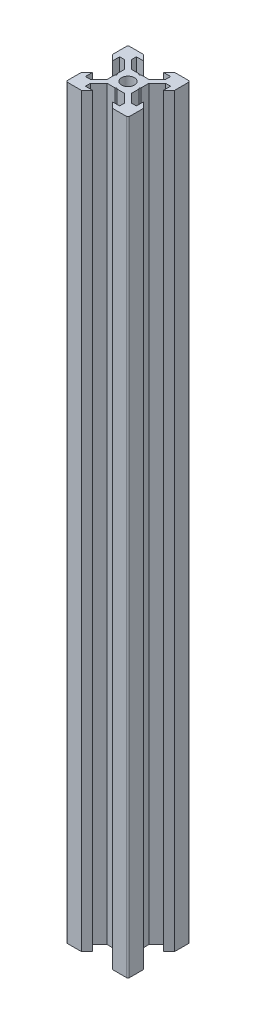
SolidWorks part; units mm, degrees
material "6063-O，挤压棒材(SS)"
ref_plane "前视基准面" through (0, 0, 0) normal (0, 0, 1) x (1, 0, 0)
ref_plane "上视基准面" through (0, 0, 0) normal (0, 1, 0) x (1, 0, 0)
ref_plane "右视基准面" through (0, 0, 0) normal (1, 0, 0) x (0, 0, -1)
other "Configuration Table"
sketch "草图1" plane through (0, 0, 0) normal (0, 1, 0) x (1, 0, 0)
  line L0 (-2.0109, 3.9) -> (2.0109, 3.9)
  line L1 (3.4251, 4.4858) -> (5.5, 6.5607)
  line L2 (5.5, 6.5607) -> (5.5, 8.2)
  line L3 (5.5, 8.2) -> (3.3, 8.2)
  line L4 (3.1, 8.4) -> (3.1, 9.3)
  line L5 (3.8, 10) -> (8.5, 10)
  line L6 (10, 8.5) -> (10, 3.8)
  line L7 (9.3, 3.1) -> (8.4, 3.1)
  line L8 (8.2, 3.3) -> (8.2, 5.5)
  line L9 (8.2, 5.5) -> (6.5607, 5.5)
  line L10 (6.5607, 5.5) -> (4.4858, 3.4251)
  line L11 (3.9, 2.0109) -> (3.9, -2.0109)
  line L12 (4.4858, -3.4251) -> (6.5607, -5.5)
  line L13 (6.5607, -5.5) -> (8.2, -5.5)
  line L14 (8.2, -5.5) -> (8.2, -3.3)
  line L15 (8.4, -3.1) -> (9.3, -3.1)
  line L16 (10, -3.8) -> (10, -8.5)
  line L17 (8.5, -10) -> (3.8, -10)
  line L18 (3.1, -9.3) -> (3.1, -8.4)
  line L19 (3.3, -8.2) -> (5.5, -8.2)
  line L20 (5.5, -8.2) -> (5.5, -6.5607)
  line L21 (5.5, -6.5607) -> (3.4251, -4.4858)
  line L22 (2.0109, -3.9) -> (-2.0109, -3.9)
  line L23 (-3.4251, -4.4858) -> (-5.5, -6.5607)
  line L24 (-5.5, -6.5607) -> (-5.5, -8.2)
  line L25 (-5.5, -8.2) -> (-3.3, -8.2)
  line L26 (-3.1, -8.4) -> (-3.1, -9.3)
  line L27 (-3.8, -10) -> (-8.5, -10)
  line L28 (-10, -8.5) -> (-10, -3.8)
  line L29 (-9.3, -3.1) -> (-8.4, -3.1)
  line L30 (-8.2, -3.3) -> (-8.2, -5.5)
  line L31 (-8.2, -5.5) -> (-6.5607, -5.5)
  line L32 (-6.5607, -5.5) -> (-4.4858, -3.4251)
  line L33 (-3.9, -2.0109) -> (-3.9, 2.0109)
  line L34 (-4.4858, 3.4251) -> (-6.5607, 5.5)
  line L35 (-6.5607, 5.5) -> (-8.2, 5.5)
  line L36 (-8.2, 5.5) -> (-8.2, 3.3)
  line L37 (-8.4, 3.1) -> (-9.3, 3.1)
  line L38 (-10, 3.8) -> (-10, 8.5)
  line L39 (-8.5, 10) -> (-3.8, 10)
  line L40 (-3.1, 9.3) -> (-3.1, 8.4)
  line L41 (-3.3, 8.2) -> (-5.5, 8.2)
  line L42 (-5.5, 8.2) -> (-5.5, 6.5607)
  line L43 (-5.5, 6.5607) -> (-3.4251, 4.4858)
  line L44 (-4.4858, 3.4251) -> (-3.4251, 4.4858) construction
  line L45 (3.4251, 4.4858) -> (4.4858, 3.4251) construction
  line L46 (4.4858, -3.4251) -> (3.4251, -4.4858) construction
  line L47 (-3.4251, -4.4858) -> (-4.4858, -3.4251) construction
  line L48 (3.9555, -3.9555) -> (-3.9555, 3.9555) construction
  line L49 (3.9555, 3.9555) -> (-3.9555, -3.9555) construction
  line L50 (-9.5, 3.3) -> (-9.5, 3.6)
  line L51 (-9.5, 3.6) -> (-9.8, 3.6)
  line L52 (-3.6, 9.8) -> (-3.6, 9.5)
  line L53 (-3.6, 9.5) -> (-3.3, 9.5)
  line L54 (3.3, 9.5) -> (3.6, 9.5)
  line L55 (3.6, 9.5) -> (3.6, 9.8)
  line L56 (9.5, 3.3) -> (9.5, 3.6)
  line L57 (9.5, 3.6) -> (9.8, 3.6)
  line L58 (9.5, -3.3) -> (9.5, -3.6)
  line L59 (9.5, -3.6) -> (9.8, -3.6)
  line L60 (3.3, -9.5) -> (3.6, -9.5)
  line L61 (3.6, -9.5) -> (3.6, -9.8)
  line L62 (-3.6, -9.8) -> (-3.6, -9.5)
  line L63 (-3.6, -9.5) -> (-3.3, -9.5)
  line L64 (-9.5, -3.3) -> (-9.5, -3.6)
  line L65 (-9.5, -3.6) -> (-9.8, -3.6)
  arc A1 (2.0109, 3.9) -> (3.4251, 4.4858) centre (2.0109, 5.9) ccw
  arc A2 (3.3, 8.2) -> (3.1, 8.4) centre (3.3, 8.4) cw
  arc A5 (8.5, 10) -> (10, 8.5) centre (8.5, 8.5) cw
  arc A8 (8.4, 3.1) -> (8.2, 3.3) centre (8.4, 3.3) cw
  arc A9 (4.4858, 3.4251) -> (3.9, 2.0109) centre (5.9, 2.0109) ccw
  arc A10 (3.9, -2.0109) -> (4.4858, -3.4251) centre (5.9, -2.0109) ccw
  arc A11 (8.2, -3.3) -> (8.4, -3.1) centre (8.4, -3.3) cw
  arc A14 (10, -8.5) -> (8.5, -10) centre (8.5, -8.5) cw
  arc A17 (3.1, -8.4) -> (3.3, -8.2) centre (3.3, -8.4) cw
  arc A18 (3.4251, -4.4858) -> (2.0109, -3.9) centre (2.0109, -5.9) ccw
  arc A19 (-2.0109, -3.9) -> (-3.4251, -4.4858) centre (-2.0109, -5.9) ccw
  arc A20 (-3.3, -8.2) -> (-3.1, -8.4) centre (-3.3, -8.4) cw
  arc A23 (-8.5, -10) -> (-10, -8.5) centre (-8.5, -8.5) cw
  arc A26 (-8.4, -3.1) -> (-8.2, -3.3) centre (-8.4, -3.3) cw
  arc A27 (-4.4858, -3.4251) -> (-3.9, -2.0109) centre (-5.9, -2.0109) ccw
  arc A28 (-3.9, 2.0109) -> (-4.4858, 3.4251) centre (-5.9, 2.0109) ccw
  arc A29 (-8.2, 3.3) -> (-8.4, 3.1) centre (-8.4, 3.3) cw
  arc A32 (-10, 8.5) -> (-8.5, 10) centre (-8.5, 8.5) cw
  arc A35 (-3.1, 8.4) -> (-3.3, 8.2) centre (-3.3, 8.4) cw
  arc A36 (-3.4251, 4.4858) -> (-2.0109, 3.9) centre (-2.0109, 5.9) ccw
  arc A37 (-9.3, 3.1) -> (-9.5, 3.3) centre (-9.3, 3.3) cw
  arc A39 (-3.8, 10) -> (-3.6, 9.8) centre (-3.8, 9.8) cw
  arc A40 (-3.3, 9.5) -> (-3.1, 9.3) centre (-3.3, 9.3) cw
  arc A41 (3.1, 9.3) -> (3.3, 9.5) centre (3.3, 9.3) cw
  arc A42 (3.6, 9.8) -> (3.8, 10) centre (3.8, 9.8) cw
  arc A43 (9.3, 3.1) -> (9.5, 3.3) centre (9.3, 3.3) ccw
  arc A44 (9.8, 3.6) -> (10, 3.8) centre (9.8, 3.8) ccw
  arc A45 (9.3, -3.1) -> (9.5, -3.3) centre (9.3, -3.3) cw
  arc A46 (9.8, -3.6) -> (10, -3.8) centre (9.8, -3.8) cw
  arc A47 (3.1, -9.3) -> (3.3, -9.5) centre (3.3, -9.3) ccw
  arc A48 (3.6, -9.8) -> (3.8, -10) centre (3.8, -9.8) ccw
  arc A49 (-3.8, -10) -> (-3.6, -9.8) centre (-3.8, -9.8) ccw
  arc A50 (-3.3, -9.5) -> (-3.1, -9.3) centre (-3.3, -9.3) ccw
  arc A51 (-9.3, -3.1) -> (-9.5, -3.3) centre (-9.3, -3.3) ccw
  arc A53 (-9.8, 3.6) -> (-10, 3.8) centre (-9.8, 3.8) cw
  arc A54 (-9.8, -3.6) -> (-10, -3.8) centre (-9.8, -3.8) ccw
  circle A55 centre (0, 0) radius 2.075
  point P119 (3.9, 0)
  dimension "D2" = 1.5
  dimension "D4" = 6.2
  dimension "D8" = 2
  dimension "D10" = 4.15
  dimension "D11" = 0.2
  dimension "D1" = 20
  dimension "D3" = 1.5
  dimension "D5" = 7.2
  dimension "D6" = 1.8
  dimension "D7" = 11
  dimension "D9" = 7.8
extrude "2020L" [suppressed] add sketch "草图1" along normal blind 240
hole_wizard "1-2020M5" [suppressed] positions "草图2" profile "草图3" tap size "M5" standard "GB"
sketch "草图2" [suppressed] plane through (0, 0, 0) normal (0, -1, 0) x (-1, 0, 0)
  point P0 (0, 0)
sketch "草图3" plane through (0, 0, 0) normal (1, 0, 0) x (0, 0, -1)
  line L0 (0, 0) -> (0, 13.6618)
  line L1 (0, 13.6618) -> (2.1, 12.4)
  line L2 (2.1, 12.4) -> (2.1, 0)
  line L5 (2.1, 0) -> (0, 0)
  line L10 (0, 13.6618) -> (-2.1, 12.4) construction
  line L11 (0, -6.35) -> (0, 107.95) construction
  dimension "螺纹孔钻头直径" = 4.2
  dimension "螺纹孔钻头深度" = 12.4
  dimension "导头角度" = 118
cosmetic thread "孔螺蚊线1" [suppressed] parameters "D1"=10, "D2"=5.2
hole_wizard "2-2020M5" [suppressed] positions "草图5" profile "草图6" tap size "M5" standard "GB"
sketch "草图5" [suppressed] plane through (0, 100, 0) normal (0, 1, 0) x (1, 0, 0)
  point P0 (0, 0)
sketch "草图6" plane through (0, 100, 0) normal (1, 0, 0) x (0, 0, 1)
  line L0 (0, 0) -> (0, 13.6618)
  line L1 (0, 13.6618) -> (2.1, 12.4)
  line L2 (2.1, 12.4) -> (2.1, 0)
  line L5 (2.1, 0) -> (0, 0)
  line L10 (0, 13.6618) -> (-2.1, 12.4) construction
  line L11 (0, -6.35) -> (0, 107.95) construction
  dimension "螺纹孔钻头直径" = 4.2
  dimension "螺纹孔钻头深度" = 12.4
  dimension "导头角度" = 118
cosmetic thread "孔螺蚊线2" [suppressed] parameters "D1"=10, "D2"=5
sketch "草图7" plane through (0, 0, 0) normal (0, 1, 0) x (1, 0, 0)
  line L88 (-10, 0) -> (10, 0) construction
  line L89 (-13.9555, 3.9555) -> (-6.0445, -3.9555) construction
  line L90 (-13.9555, -3.9555) -> (-6.0445, 3.9555) construction
  line L91 (6.0445, 3.9555) -> (13.9555, -3.9555) construction
  line L92 (6.0445, -3.9555) -> (13.9555, 3.9555) construction
  line L93 (-7.9891, 3.9) -> (-12.0109, 3.9)
  line L94 (-13.4251, 4.4858) -> (-15.5, 6.5607)
  line L95 (-15.5, 6.5607) -> (-15.5, 8.2)
  line L96 (-15.5, 8.2) -> (-13.1, 8.2)
  line L97 (-13.1, 8.2) -> (-13.1, 9.5)
  line L98 (-13.1, 9.5) -> (-13.6, 9.5)
  line L99 (-13.6, 9.5) -> (-13.6, 10)
  line L100 (-13.6, 10) -> (-18.5, 10)
  line L101 (-20, 8.5) -> (-20, 3.6)
  line L102 (-20, 3.6) -> (-19.5, 3.6)
  line L103 (-19.5, 3.6) -> (-19.5, 3.1)
  line L104 (-19.5, 3.1) -> (-18.2, 3.1)
  line L105 (-18.2, 3.1) -> (-18.2, 5.5)
  line L106 (-18.2, 5.5) -> (-16.5607, 5.5)
  line L107 (-16.5607, 5.5) -> (-14.4858, 3.4251)
  line L108 (-13.9, 2.0109) -> (-13.9, -2.0109)
  line L109 (-14.4858, -3.4251) -> (-16.5607, -5.5)
  line L110 (-16.5607, -5.5) -> (-18.2, -5.5)
  line L111 (-18.2, -5.5) -> (-18.2, -3.1)
  line L112 (-18.2, -3.1) -> (-19.5, -3.1)
  line L113 (-19.5, -3.1) -> (-19.5, -3.6)
  line L114 (-19.5, -3.6) -> (-20, -3.6)
  line L115 (-20, -3.6) -> (-20, -8.5)
  line L116 (-18.5, -10) -> (-13.6, -10)
  line L117 (-13.6, -10) -> (-13.6, -9.5)
  line L118 (-13.6, -9.5) -> (-13.1, -9.5)
  line L119 (-13.1, -9.5) -> (-13.1, -8.2)
  line L120 (-13.1, -8.2) -> (-15.5, -8.2)
  line L121 (-15.5, -8.2) -> (-15.5, -6.5607)
  line L122 (-15.5, -6.5607) -> (-13.4251, -4.4858)
  line L123 (-12.0109, -3.9) -> (-7.9891, -3.9)
  line L124 (-6.5749, -4.4858) -> (-4.5, -6.5607)
  line L125 (-4.5, -6.5607) -> (-4.5, -8.2)
  line L126 (-4.5, -8.2) -> (-6.9, -8.2)
  line L127 (-6.9, -8.2) -> (-6.9, -9.5)
  line L128 (-6.9, -9.5) -> (-6.4, -9.5)
  line L129 (-6.4, -9.5) -> (-6.4, -10)
  line L130 (-6.4, -10) -> (6.4, -10)
  line L131 (6.4, -10) -> (6.4, -9.5)
  line L132 (6.4, -9.5) -> (6.9, -9.5)
  line L133 (6.9, -9.5) -> (6.9, -8.2)
  line L134 (6.9, -8.2) -> (4.5, -8.2)
  line L135 (4.5, -8.2) -> (4.5, -6.5607)
  line L136 (4.5, -6.5607) -> (6.5749, -4.4858)
  line L137 (7.9891, -3.9) -> (12.0109, -3.9)
  line L138 (13.4251, -4.4858) -> (15.5, -6.5607)
  line L139 (15.5, -6.5607) -> (15.5, -8.2)
  line L140 (15.5, -8.2) -> (13.1, -8.2)
  line L141 (13.1, -8.2) -> (13.1, -9.5)
  line L142 (13.1, -9.5) -> (13.6, -9.5)
  line L143 (13.6, -9.5) -> (13.6, -10)
  line L144 (13.6, -10) -> (18.5, -10)
  line L145 (20, -8.5) -> (20, -3.6)
  line L146 (20, -3.6) -> (19.5, -3.6)
  line L147 (19.5, -3.6) -> (19.5, -3.1)
  line L148 (19.5, -3.1) -> (18.2, -3.1)
  line L149 (18.2, -3.1) -> (18.2, -5.5)
  line L150 (18.2, -5.5) -> (16.5607, -5.5)
  line L151 (16.5607, -5.5) -> (14.4858, -3.4251)
  line L152 (13.9, -2.0109) -> (13.9, 2.0109)
  line L153 (14.4858, 3.4251) -> (16.5607, 5.5)
  line L154 (16.5607, 5.5) -> (18.2, 5.5)
  line L155 (18.2, 5.5) -> (18.2, 3.1)
  line L156 (18.2, 3.1) -> (19.5, 3.1)
  line L157 (19.5, 3.1) -> (19.5, 3.6)
  line L158 (19.5, 3.6) -> (20, 3.6)
  line L159 (20, 3.6) -> (20, 8.5)
  line L160 (18.5, 10) -> (13.6, 10)
  line L161 (13.6, 10) -> (13.6, 9.5)
  line L162 (13.6, 9.5) -> (13.1, 9.5)
  line L163 (13.1, 9.5) -> (13.1, 8.2)
  line L164 (13.1, 8.2) -> (15.5, 8.2)
  line L165 (15.5, 8.2) -> (15.5, 6.5607)
  line L166 (15.5, 6.5607) -> (13.4251, 4.4858)
  line L167 (12.0109, 3.9) -> (7.9891, 3.9)
  line L168 (6.5749, 4.4858) -> (4.5, 6.5607)
  line L169 (4.5, 6.5607) -> (4.5, 8.2)
  line L170 (4.5, 8.2) -> (6.9, 8.2)
  line L171 (6.9, 8.2) -> (6.9, 9.5)
  line L172 (6.9, 9.5) -> (6.4, 9.5)
  line L173 (6.4, 9.5) -> (6.4, 10)
  line L174 (6.4, 10) -> (-6.4, 10)
  line L175 (-6.4, 10) -> (-6.4, 9.5)
  line L176 (-6.4, 9.5) -> (-6.9, 9.5)
  line L177 (-6.9, 9.5) -> (-6.9, 8.2)
  line L178 (-6.9, 8.2) -> (-4.5, 8.2)
  line L179 (-4.5, 8.2) -> (-4.5, 6.5607)
  line L180 (-4.5, 6.5607) -> (-6.5749, 4.4858)
  line L181 (-14.4858, 3.4251) -> (-13.4251, 4.4858) construction
  line L182 (-14.4858, -3.4251) -> (-13.4251, -4.4858) construction
  line L183 (13.4251, -4.4858) -> (14.4858, -3.4251) construction
  line L184 (13.4251, 4.4858) -> (14.4858, 3.4251) construction
  line L185 (-2.3787, 8.2) -> (2.3787, 8.2)
  line L186 (2.3787, 8.2) -> (2.3787, 6.5607)
  line L187 (2.3787, 6.5607) -> (5.5142, 3.4251)
  line L188 (6.1, 2.0109) -> (6.1, -2.0109)
  line L189 (5.5142, -3.4251) -> (2.3787, -6.5607)
  line L190 (2.3787, -6.5607) -> (2.3787, -8.2)
  line L191 (2.3787, -8.2) -> (-2.3787, -8.2)
  line L192 (-2.3787, -8.2) -> (-2.3787, -6.5607)
  line L193 (-2.3787, -6.5607) -> (-5.5142, -3.4251)
  line L194 (-6.1, -2.0109) -> (-6.1, 2.0109)
  line L195 (-5.5142, 3.4251) -> (-2.3787, 6.5607)
  line L196 (-2.3787, 6.5607) -> (-2.3787, 8.2)
  line L197 (-6.5749, 4.4858) -> (-5.5142, 3.4251) construction
  line L198 (-6.5749, -4.4858) -> (-5.5142, -3.4251) construction
  line L199 (5.5142, 3.4251) -> (6.5749, 4.4858) construction
  line L200 (5.5142, -3.4251) -> (6.5749, -4.4858) construction
  arc A16 (-12.0109, 3.9) -> (-13.4251, 4.4858) centre (-12.0109, 5.9) cw
  arc A17 (-18.5, 10) -> (-20, 8.5) centre (-18.5, 8.5) ccw
  arc A18 (-14.4858, 3.4251) -> (-13.9, 2.0109) centre (-15.9, 2.0109) cw
  arc A19 (-13.9, -2.0109) -> (-14.4858, -3.4251) centre (-15.9, -2.0109) cw
  arc A20 (-20, -8.5) -> (-18.5, -10) centre (-18.5, -8.5) ccw
  arc A21 (-13.4251, -4.4858) -> (-12.0109, -3.9) centre (-12.0109, -5.9) cw
  arc A22 (-7.9891, -3.9) -> (-6.5749, -4.4858) centre (-7.9891, -5.9) cw
  arc A23 (6.5749, -4.4858) -> (7.9891, -3.9) centre (7.9891, -5.9) cw
  arc A24 (12.0109, -3.9) -> (13.4251, -4.4858) centre (12.0109, -5.9) cw
  arc A25 (18.5, -10) -> (20, -8.5) centre (18.5, -8.5) ccw
  arc A26 (14.4858, -3.4251) -> (13.9, -2.0109) centre (15.9, -2.0109) cw
  arc A27 (13.9, 2.0109) -> (14.4858, 3.4251) centre (15.9, 2.0109) cw
  arc A28 (20, 8.5) -> (18.5, 10) centre (18.5, 8.5) ccw
  arc A29 (13.4251, 4.4858) -> (12.0109, 3.9) centre (12.0109, 5.9) cw
  arc A30 (7.9891, 3.9) -> (6.5749, 4.4858) centre (7.9891, 5.9) cw
  arc A31 (-6.5749, 4.4858) -> (-7.9891, 3.9) centre (-7.9891, 5.9) cw
  arc A32 (5.5142, 3.4251) -> (6.1, 2.0109) centre (4.1, 2.0109) cw
  arc A33 (6.1, -2.0109) -> (5.5142, -3.4251) centre (4.1, -2.0109) cw
  arc A34 (-5.5142, -3.4251) -> (-6.1, -2.0109) centre (-4.1, -2.0109) cw
  arc A35 (-6.1, 2.0109) -> (-5.5142, 3.4251) centre (-4.1, 2.0109) cw
  circle A36 centre (-10, 0) radius 2.075
  circle A37 centre (10, 0) radius 2.075
  point P177 (0, 10)
  point P178 (0, -10)
  dimension "D5" = 2
  dimension "D8" = 1.5
  dimension "D13" = 4.15
  dimension "D1" = 20
  dimension "D2" = 45
  dimension "D3" = 45
  dimension "D4" = 7.8
  dimension "D6" = 1.5
  dimension "D7" = 40
  dimension "D9" = 6.2
  dimension "D10" = 7.2
  dimension "D11" = 1.8
  dimension "D12" = 11
extrude "2040L" [suppressed] add sketch "草图7" along normal blind 240
fillet "圆角1" [suppressed] radius 0.25
sketch "草图8" [suppressed] plane through (0, 0, 0) normal (0, -1, 0) x (1, 0, 0)
  circle A0 centre (10, 0) radius 2.075 construction
  circle A1 centre (-10, 0) radius 2.075 construction
  point P0 (-10, 0)
  point P1 (10, 0)
hole_wizard "1-2040M5" [suppressed] positions "草图13" profile "草图14" tap size "M5" standard "GB"
sketch "草图13" [suppressed] plane through (0, 0, 0) normal (0, -1, 0) x (-1, 0, 0)
  point P0 (-10, 0)
sketch "草图14" plane through (10, 0, 0) normal (1, 0, 0) x (0, 0, -1)
  line L0 (0, 0) -> (0, 13.6618)
  line L1 (0, 13.6618) -> (2.1, 12.4)
  line L2 (2.1, 12.4) -> (2.1, 0)
  line L5 (2.1, 0) -> (0, 0)
  line L10 (0, 13.6618) -> (-2.1, 12.4) construction
  line L11 (0, -6.35) -> (0, 107.95) construction
  dimension "螺纹孔钻头直径" = 4.2
  dimension "螺纹孔钻头深度" = 12.4
  dimension "导头角度" = 118
cosmetic thread "孔螺蚊线7" [suppressed] parameters "D1"=10, "D2"=5
hole_wizard "2-2040M5" [suppressed] positions "草图15" profile "草图16" tap size "M5" standard "GB"
sketch "草图15" [suppressed] plane through (0, 0, 0) normal (0, -1, 0) x (-1, 0, 0)
  point P0 (10, 0)
sketch "草图16" plane through (-10, 0, 0) normal (1, 0, 0) x (0, 0, -1)
  line L0 (0, 0) -> (0, 13.6618)
  line L1 (0, 13.6618) -> (2.1, 12.4)
  line L2 (2.1, 12.4) -> (2.1, 0)
  line L5 (2.1, 0) -> (0, 0)
  line L10 (0, 13.6618) -> (-2.1, 12.4) construction
  line L11 (0, -6.35) -> (0, 107.95) construction
  dimension "螺纹孔钻头直径" = 4.2
  dimension "螺纹孔钻头深度" = 12.4
  dimension "导头角度" = 118
cosmetic thread "孔螺蚊线8" [suppressed] parameters "D1"=10, "D2"=5
hole_wizard "3-2040M5" [suppressed] positions "草图19" profile "草图20" tap size "M5" standard "GB"
sketch "草图19" [suppressed] plane through (0, 100, 0) normal (0, 1, 0) x (1, 0, 0)
  point P0 (10, 0)
sketch "草图20" plane through (10, 100, 0) normal (1, 0, 0) x (0, 0, 1)
  line L0 (0, 0) -> (0, 13.6618)
  line L1 (0, 13.6618) -> (2.1, 12.4)
  line L2 (2.1, 12.4) -> (2.1, 0)
  line L5 (2.1, 0) -> (0, 0)
  line L10 (0, 13.6618) -> (-2.1, 12.4) construction
  line L11 (0, -6.35) -> (0, 107.95) construction
  dimension "螺纹孔钻头直径" = 4.2
  dimension "螺纹孔钻头深度" = 12.4
  dimension "导头角度" = 118
cosmetic thread "孔螺蚊线10" [suppressed] parameters "D1"=10, "D2"=5
hole_wizard "4-2040M5" [suppressed] positions "草图21" profile "草图22" tap size "M5" standard "GB"
sketch "草图21" [suppressed] plane through (0, 100, 0) normal (0, 1, 0) x (1, 0, 0)
  point P0 (-10, 0)
sketch "草图22" plane through (-10, 100, 0) normal (1, 0, 0) x (0, 0, 1)
  line L0 (0, 0) -> (0, 13.6618)
  line L1 (0, 13.6618) -> (2.1, 12.4)
  line L2 (2.1, 12.4) -> (2.1, 0)
  line L5 (2.1, 0) -> (0, 0)
  line L10 (0, 13.6618) -> (-2.1, 12.4) construction
  line L11 (0, -6.35) -> (0, 107.95) construction
  dimension "螺纹孔钻头直径" = 4.2
  dimension "螺纹孔钻头深度" = 12.4
  dimension "导头角度" = 118
cosmetic thread "孔螺蚊线11" [suppressed] parameters "D1"=10, "D2"=5
sketch "草图23" plane through (0, 0, 0) normal (0, 1, 0) x (1, 0, 0)
  line L0 (-3.9, 2.0109) -> (-3.9, -2.0109)
  line L1 (-4.4858, -3.4251) -> (-6.5607, -5.5)
  line L2 (-6.5607, -5.5) -> (-8.2, -5.5)
  line L3 (-8.2, -5.5) -> (-8.2, -3.1)
  line L4 (-8.2, -3.1) -> (-9.5, -3.1)
  line L5 (-9.5, -3.1) -> (-9.5, -3.6)
  line L6 (-9.5, -3.6) -> (-10, -3.6)
  line L7 (-10, -3.6) -> (-10, -8.5)
  line L8 (-8.5, -10) -> (-3.6, -10)
  line L9 (-3.6, -10) -> (-3.6, -9.5)
  line L10 (-3.6, -9.5) -> (-3.1, -9.5)
  line L11 (-3.1, -9.5) -> (-3.1, -8.2)
  line L12 (-3.1, -8.2) -> (-5.5, -8.2)
  line L13 (-5.5, -8.2) -> (-5.5, -6.5607)
  line L14 (-5.5, -6.5607) -> (-3.4251, -4.4858)
  line L15 (-2.0109, -3.9) -> (2.0109, -3.9)
  line L16 (3.4251, -4.4858) -> (5.5, -6.5607)
  line L17 (5.5, -6.5607) -> (5.5, -8.2)
  line L18 (5.5, -8.2) -> (3.1, -8.2)
  line L19 (3.1, -8.2) -> (3.1, -9.5)
  line L20 (3.1, -9.5) -> (3.6, -9.5)
  line L21 (3.6, -9.5) -> (3.6, -10)
  line L22 (3.6, -10) -> (8.5, -10)
  line L23 (-10, 8.5) -> (-10, 3.6)
  line L24 (-10, 3.6) -> (-9.5, 3.6)
  line L25 (-9.5, 3.6) -> (-9.5, 3.1)
  line L26 (-9.5, 3.1) -> (-8.2, 3.1)
  line L27 (-8.2, 3.1) -> (-8.2, 5.5)
  line L28 (-8.2, 5.5) -> (-6.5607, 5.5)
  line L29 (-6.5607, 5.5) -> (-4.4858, 3.4251)
  line L30 (-3.9555, -3.9555) -> (3.9555, 3.9555) construction
  line L31 (-3.9555, 3.9555) -> (3.9555, -3.9555) construction
  line L32 (-4.4858, -3.4251) -> (-3.4251, -4.4858) construction
  line L39 (-4.4858, 3.4251) -> (-3.4251, 4.4858) construction
  line L40 (3.4251, -4.4858) -> (4.4858, -3.4251) construction
  line L41 (-3.4251, 4.4858) -> (-5.5, 6.5607)
  line L42 (-5.5, 6.5607) -> (-5.5, 8.2332)
  line L43 (2.6122, 3.9) -> (-2.0109, 3.9)
  line L44 (3.9, 2.6122) -> (3.9, -2.0109)
  line L45 (6.5607, -5.5) -> (8.2332, -5.5)
  line L46 (4.4858, -3.4251) -> (6.5607, -5.5)
  arc A0 (-3.9, -2.0109) -> (-4.4858, -3.4251) centre (-5.9, -2.0109) cw
  arc A1 (-10, -8.5) -> (-8.5, -10) centre (-8.5, -8.5) ccw
  arc A2 (-3.4251, -4.4858) -> (-2.0109, -3.9) centre (-2.0109, -5.9) cw
  arc A3 (2.0109, -3.9) -> (3.4251, -4.4858) centre (2.0109, -5.9) cw
  arc A4 (8.5, -10) -> (10, -8.5) centre (8.5, -8.5) ccw
  arc A5 (10, -8.5) -> (-8.5, 10) centre (-8.5, -8.5) ccw
  arc A6 (-8.5, 10) -> (-10, 8.5) centre (-8.5, 8.5) ccw
  arc A7 (-4.4858, 3.4251) -> (-3.9, 2.0109) centre (-5.9, 2.0109) cw
  arc A14 (-5.5, 8.2332) -> (2.7444, 4.25) centre (-8.5, -8.5) cw
  arc A15 (2.7444, 4.25) -> (2.6122, 3.9) centre (2.6122, 4.1) cw
  arc A16 (-2.0109, 3.9) -> (-3.4251, 4.4858) centre (-2.0109, 5.9) cw
  arc A17 (4.25, 2.7444) -> (3.9, 2.6122) centre (4.1, 2.6122) ccw
  arc A18 (8.2332, -5.5) -> (4.25, 2.7444) centre (-8.5, -8.5) ccw
  arc A19 (3.9, -2.0109) -> (4.4858, -3.4251) centre (5.9, -2.0109) ccw
  circle A20 centre (0, 0) radius 2.075
  dimension "D3" = 1.5
  dimension "D5" = 2
  dimension "D10" = 17
  dimension "D11" = 0.2
  dimension "D12" = 4.15
  dimension "D1" = 20
  dimension "D2" = 1.5
  dimension "D4" = 11
  dimension "D6" = 1.8
  dimension "D7" = 3.9
  dimension "D8" = 6.2
  dimension "D9" = 7.2
extrude "2020R" [suppressed] add sketch "草图23" along normal blind 240
fillet "圆角2" [suppressed] radius 0.25
hole_wizard "1-2020R" [suppressed] positions "草图24" profile "草图25" tap size "M5" standard "GB"
sketch "草图24" [suppressed] plane through (0, 100, 0) normal (0, 1, 0) x (1, 0, 0)
  point P0 (0, 0)
sketch "草图25" plane through (0, 100, 0) normal (1, 0, 0) x (0, 0, 1)
  line L0 (0, 0) -> (0, 13.6618)
  line L1 (0, 13.6618) -> (2.1, 12.4)
  line L2 (2.1, 12.4) -> (2.1, 0)
  line L5 (2.1, 0) -> (0, 0)
  line L10 (0, 13.6618) -> (-2.1, 12.4) construction
  line L11 (0, -6.35) -> (0, 107.95) construction
  dimension "螺纹孔钻头直径" = 4.2
  dimension "螺纹孔钻头深度" = 12.4
  dimension "导头角度" = 118
cosmetic thread "孔螺蚊线12" parameters "D1"=10, "D2"=5
hole_wizard "2-2020R" [suppressed] positions "草图26" profile "草图27" tap size "M5" standard "GB"
sketch "草图26" [suppressed] plane through (0, 0, 0) normal (0, -1, 0) x (-1, 0, 0)
  point P0 (0, 0)
sketch "草图27" plane through (0, 0, 0) normal (1, 0, 0) x (0, 0, -1)
  line L0 (0, 0) -> (0, 13.6618)
  line L1 (0, 13.6618) -> (2.1, 12.4)
  line L2 (2.1, 12.4) -> (2.1, 0)
  line L5 (2.1, 0) -> (0, 0)
  line L10 (0, 13.6618) -> (-2.1, 12.4) construction
  line L11 (0, -6.35) -> (0, 107.95) construction
  dimension "螺纹孔钻头直径" = 4.2
  dimension "螺纹孔钻头深度" = 12.4
  dimension "导头角度" = 118
cosmetic thread "孔螺蚊线13" parameters "D1"=10, "D2"=5
sketch "草图28" plane through (0, 0, 0) normal (0, 1, 0) x (1, 0, 0)
  line L56 (-3.9, 2.8393) -> (-3.9, 0.2828)
  line L57 (-3.9, 0.2828) -> (-3.6172, 0)
  line L58 (-3.6172, 0) -> (-3.9, -0.2828)
  line L59 (-3.9, -0.2828) -> (-3.9, -2.8393)
  line L60 (-3.9, -2.8393) -> (-6.5607, -5.5)
  line L61 (-6.5607, -5.5) -> (-8.2, -5.5)
  line L62 (-8.2, -5.5) -> (-8.2, -3.15)
  line L63 (-8.2, -3.15) -> (-10, -4.95)
  line L64 (-10, -4.95) -> (-10, -9.5)
  line L65 (-9.5, -10) -> (-4.95, -10)
  line L66 (-4.95, -10) -> (-3.15, -8.2)
  line L67 (-3.15, -8.2) -> (-5.5, -8.2)
  line L68 (-5.5, -8.2) -> (-5.5, -6.5607)
  line L69 (-5.5, -6.5607) -> (-2.8393, -3.9)
  line L70 (-2.8393, -3.9) -> (-0.2828, -3.9)
  line L71 (-0.2828, -3.9) -> (0, -3.6172)
  line L72 (0, -3.6172) -> (0.2828, -3.9)
  line L73 (0.2828, -3.9) -> (2.8393, -3.9)
  line L74 (2.8393, -3.9) -> (5.5, -6.5607)
  line L75 (5.5, -6.5607) -> (5.5, -8.2)
  line L76 (5.5, -8.2) -> (3.15, -8.2)
  line L77 (3.15, -8.2) -> (4.95, -10)
  line L78 (4.95, -10) -> (9.5, -10)
  line L79 (10, -9.5) -> (10, -4.95)
  line L80 (10, -4.95) -> (8.2, -3.15)
  line L81 (8.2, -3.15) -> (8.2, -5.5)
  line L82 (8.2, -5.5) -> (6.5607, -5.5)
  line L83 (6.5607, -5.5) -> (3.9, -2.8393)
  line L84 (3.9, -2.8393) -> (3.9, -0.2828)
  line L85 (3.9, -0.2828) -> (3.6172, 0)
  line L86 (3.6172, 0) -> (3.9, 0.2828)
  line L87 (3.9, 0.2828) -> (3.9, 2.8393)
  line L88 (3.9, 2.8393) -> (6.5607, 5.5)
  line L89 (6.5607, 5.5) -> (8.2, 5.5)
  line L90 (8.2, 5.5) -> (8.2, 3.15)
  line L91 (8.2, 3.15) -> (10, 4.95)
  line L92 (10, 4.95) -> (10, 9.5)
  line L93 (9.5, 10) -> (4.95, 10)
  line L94 (4.95, 10) -> (3.15, 8.2)
  line L95 (3.15, 8.2) -> (5.5, 8.2)
  line L96 (5.5, 8.2) -> (5.5, 6.5607)
  line L97 (5.5, 6.5607) -> (2.8393, 3.9)
  line L98 (2.8393, 3.9) -> (0.2828, 3.9)
  line L99 (0.2828, 3.9) -> (0, 3.6172)
  line L100 (0, 3.6172) -> (-0.2828, 3.9)
  line L101 (-0.2828, 3.9) -> (-2.8393, 3.9)
  line L102 (-2.8393, 3.9) -> (-5.5, 6.5607)
  line L103 (-5.5, 6.5607) -> (-5.5, 8.2)
  line L104 (-5.5, 8.2) -> (-3.15, 8.2)
  line L105 (-3.15, 8.2) -> (-4.95, 10)
  line L106 (-4.95, 10) -> (-9.5, 10)
  line L107 (-10, 9.5) -> (-10, 4.95)
  line L108 (-10, 4.95) -> (-8.2, 3.15)
  line L109 (-8.2, 3.15) -> (-8.2, 5.5)
  line L110 (-8.2, 5.5) -> (-6.5607, 5.5)
  line L111 (-6.5607, 5.5) -> (-3.9, 2.8393)
  line L112 (-2.8393, 3.9) -> (-3.9, 2.8393) construction
  line L113 (-3.9, -2.8393) -> (-2.8393, -3.9) construction
  line L114 (2.8393, -3.9) -> (3.9, -2.8393) construction
  line L115 (2.8393, 3.9) -> (3.9, 2.8393) construction
  line L116 (-3.3697, 3.3697) -> (3.3697, -3.3697) construction
  line L117 (-3.3697, -3.3697) -> (3.3697, 3.3697) construction
  arc A4 (-10, -9.5) -> (-9.5, -10) centre (-9.5, -9.5) ccw
  arc A5 (9.5, -10) -> (10, -9.5) centre (9.5, -9.5) ccw
  arc A6 (10, 9.5) -> (9.5, 10) centre (9.5, 9.5) ccw
  arc A7 (-9.5, 10) -> (-10, 9.5) centre (-9.5, 9.5) ccw
  circle A8 centre (0, 0) radius 2.075
  dimension "D7" = 0.5
  dimension "D9" = 4.15
  dimension "D1" = 7.8
  dimension "D2" = 20
  dimension "D3" = 1.5
  dimension "D4" = 0.4
  dimension "D5" = 11
  dimension "D6" = 6.3
  dimension "D8" = 1.8
extrude "2020V" add sketch "草图28" along normal blind 240
hole_wizard "1-2020V" [suppressed] positions "草图29" profile "草图30" tap size "M5" standard "GB"
sketch "草图29" plane through (0, 100, 0) normal (0, 1, 0) x (1, 0, 0)
  point P0 (0, 0)
sketch "草图30" plane through (0, 100, 0) normal (1, 0, 0) x (0, 0, 1)
  line L0 (0, 0) -> (0, 13.6618)
  line L1 (0, 13.6618) -> (2.1, 12.4)
  line L2 (2.1, 12.4) -> (2.1, 0)
  line L5 (2.1, 0) -> (0, 0)
  line L10 (0, 13.6618) -> (-2.1, 12.4) construction
  line L11 (0, -6.35) -> (0, 107.95) construction
  dimension "螺纹孔钻头直径" = 4.2
  dimension "螺纹孔钻头深度" = 12.4
  dimension "导头角度" = 118
cosmetic thread "孔螺蚊线14" [suppressed] parameters "D1"=10, "D2"=5
hole_wizard "2-2020V" [suppressed] positions "草图31" profile "草图32" tap size "M5" standard "GB"
sketch "草图31" plane through (0, 0, 0) normal (0, -1, 0) x (-1, 0, 0)
  point P0 (0, 0)
sketch "草图32" plane through (0, 0, 0) normal (1, 0, 0) x (0, 0, -1)
  line L0 (0, 0) -> (0, 13.6618)
  line L1 (0, 13.6618) -> (2.1, 12.4)
  line L2 (2.1, 12.4) -> (2.1, 0)
  line L5 (2.1, 0) -> (0, 0)
  line L10 (0, 13.6618) -> (-2.1, 12.4) construction
  line L11 (0, -6.35) -> (0, 107.95) construction
  dimension "螺纹孔钻头直径" = 4.2
  dimension "螺纹孔钻头深度" = 12.4
  dimension "导头角度" = 118
cosmetic thread "孔螺蚊线15" [suppressed] parameters "D1"=10, "D2"=5
equation "\"L\" = 240'型材长度"
equation "\"L@2020L\" = \"L\""
equation "\"L@2040L\" = \"L\""
equation "\"L@2020R\"= \"L\""
equation "\"L@2020V\"= \"L\""
